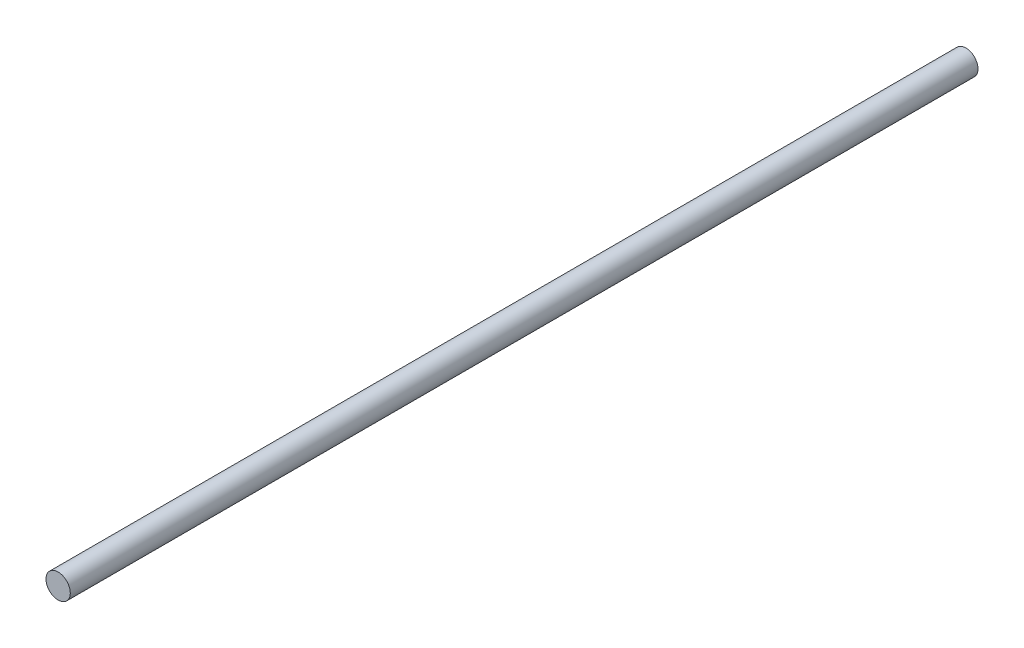
SolidWorks part; units mm, degrees
material "Thornel Mat VMA"
ref_plane "Front Plane" through (0, 0, 0) normal (0, 0, 1) x (1, 0, 0)
ref_plane "Top Plane" through (0, 0, 0) normal (0, 1, 0) x (1, 0, 0)
ref_plane "Right Plane" through (0, 0, 0) normal (1, 0, 0) x (0, 0, -1)
sketch "Sketch1" plane through (0, 0, 0) normal (0, 0, 1) x (1, 0, 0)
  circle A0 centre (0, 0) radius 5
  dimension "D1" = 10
extrude "Boss-Extrude1" add sketch "Sketch1" along normal blind 373.35
